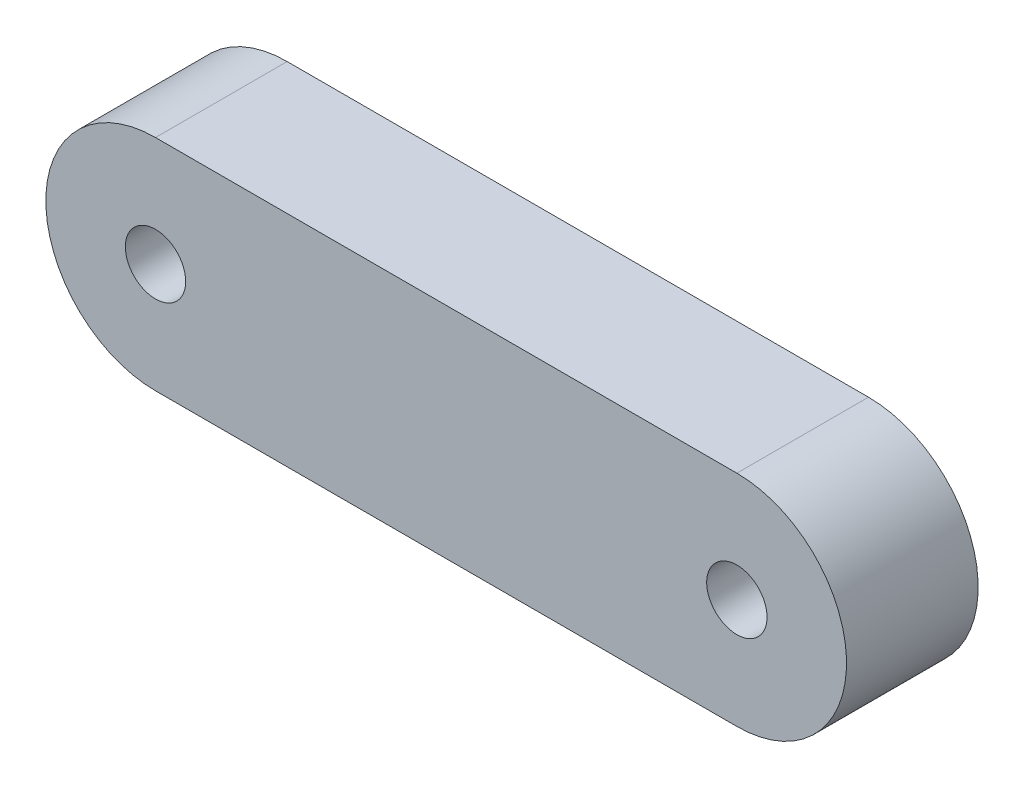
SolidWorks part; units mm, degrees
ref_plane "Front Plane" through (0, 0, 0) normal (0, 0, 1) x (1, 0, 0)
ref_plane "Top Plane" through (0, 0, 0) normal (0, 1, 0) x (1, 0, 0)
ref_plane "Right Plane" through (0, 0, 0) normal (1, 0, 0) x (0, 0, -1)
sketch "Sketch1" plane through (0, 0, 0) normal (0, 0, 1) x (1, 0, 0)
  line L0 (0, 0) -> (-53, 0) construction
  line L1 (0, -10) -> (-53, -10)
  line L2 (0, 10) -> (-53, 10)
  arc A0 (0, -10) -> (0, 10) centre (0, 0) ccw
  arc A1 (-53, 10) -> (-53, -10) centre (-53, 0) ccw
  circle A2 centre (-53, 0) radius 2.75
  circle A3 centre (0, 0) radius 2.75
  point P3 (-26.5, 0)
  dimension "D3" = 5.5
  dimension "D4" = 5.5
  dimension "D1" = 53
  dimension "D2" = 20
extrude "Boss-Extrude1" add sketch "Sketch1" along normal blind 12
